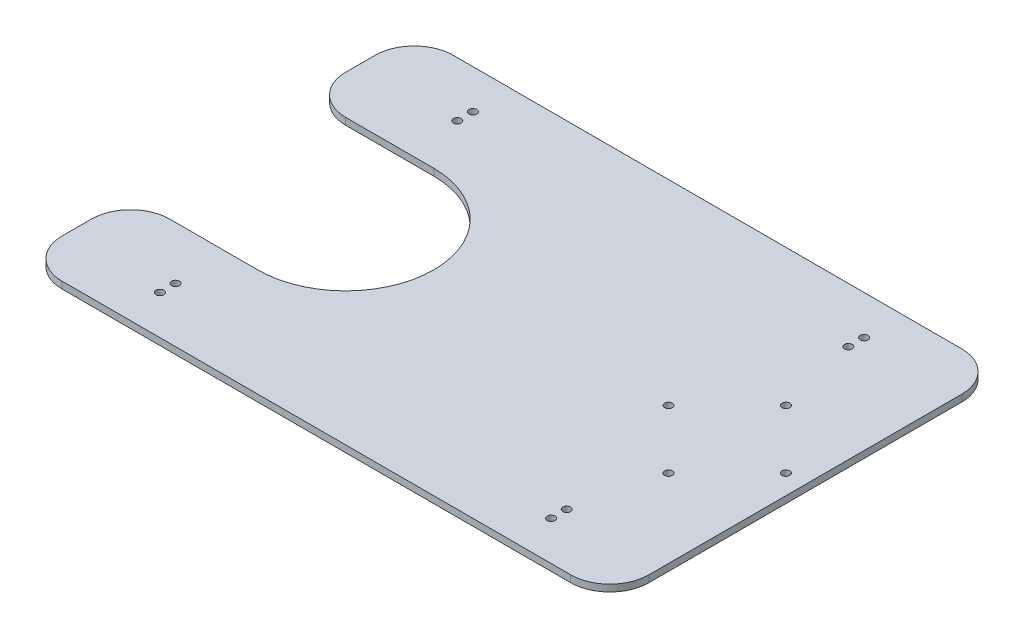
SolidWorks part; units mm, degrees
ref_plane "Front Plane" through (0, 0, 0) normal (0, 0, 1) x (1, 0, 0)
ref_plane "Top Plane" through (0, 0, 0) normal (0, 1, 0) x (1, 0, 0)
ref_plane "Right Plane" through (0, 0, 0) normal (1, 0, 0) x (0, 0, -1)
sketch "Sketch1" plane through (0, 0, 0) normal (0, 1, 0) x (1, 0, 0)
  line L0 (-150, 100) -> (-150, 45)
  line L1 (-150, 100) -> (150, 100)
  line L3 (-150, -100) -> (150, -100)
  line L4 (150, 100) -> (150, -100)
  line L5 (-150, 100) -> (150, -100) construction
  line L6 (-150, -100) -> (150, 100) construction
  line L7 (-150, 45) -> (-85, 45)
  line L9 (-85, -45) -> (-150, -45)
  line L10 (-150, -45) -> (-150, -100)
  line L11 (110, 0) -> (110, 30) construction
  line L12 (-100, 80) -> (100, 80) construction
  line L13 (-100, 80) -> (-100, -80) construction
  line L14 (-100, -80) -> (100, -80) construction
  line L15 (100, 80) -> (100, -80) construction
  line L16 (-100, 80) -> (100, -80) construction
  line L17 (-100, -80) -> (100, 80) construction
  arc A0 (-85, 45) -> (-85, -45) centre (-85, 0) cw
  circle A1 centre (-100, 80) radius 2
  circle A2 centre (100, 80) radius 2
  circle A3 centre (100, -80) radius 2
  circle A4 centre (-100, -80) radius 2
  circle A5 centre (-100, 72) radius 2
  circle A6 centre (100, 72) radius 2
  circle A7 centre (100, -72) radius 2
  circle A8 centre (-100, -72) radius 2
  arc A9 (100, 28.2843) -> (100, -28.2843) centre (110, 0) ccw construction
  arc A10 (100, -28.2843) -> (100, 28.2843) centre (110, 0) ccw construction
  circle A11 centre (110, 30) radius 2
  circle A12 centre (140, 0) radius 2
  circle A13 centre (110, -30) radius 2
  circle A14 centre (80, 0) radius 2
  point P0 (0, 0)
  point P11 (0, 0)
  dimension "D4" = 65
  dimension "D3" = 45
  dimension "D7" = 4
  dimension "D8" = 4
  dimension "D9" = 4
  dimension "D10" = 4
  dimension "D12" = 4
  dimension "D14" = 4
  dimension "D16" = 4
  dimension "D18" = 4
  dimension "D19" = 60
  dimension "D21" = 4
  dimension "D1" = 300
  dimension "D2" = 200
  dimension "D5" = 160
  dimension "D6" = 200
  dimension "D11" = 8
  dimension "D13" = 8
  dimension "D15" = 8
  dimension "D17" = 8
  dimension "D20" = 40
  dimension "D22" = 4
extrude "Boss-Extrude1" add sketch "Sketch1" along normal mid plane 3.5
fillet "Fillet1" radius 20 6 edges at (-150, 0, 100) (-150, 0, 45) (-150, 0, -45) (-150, 0, -100) (150, 0, -100) (150, 0, 100)
